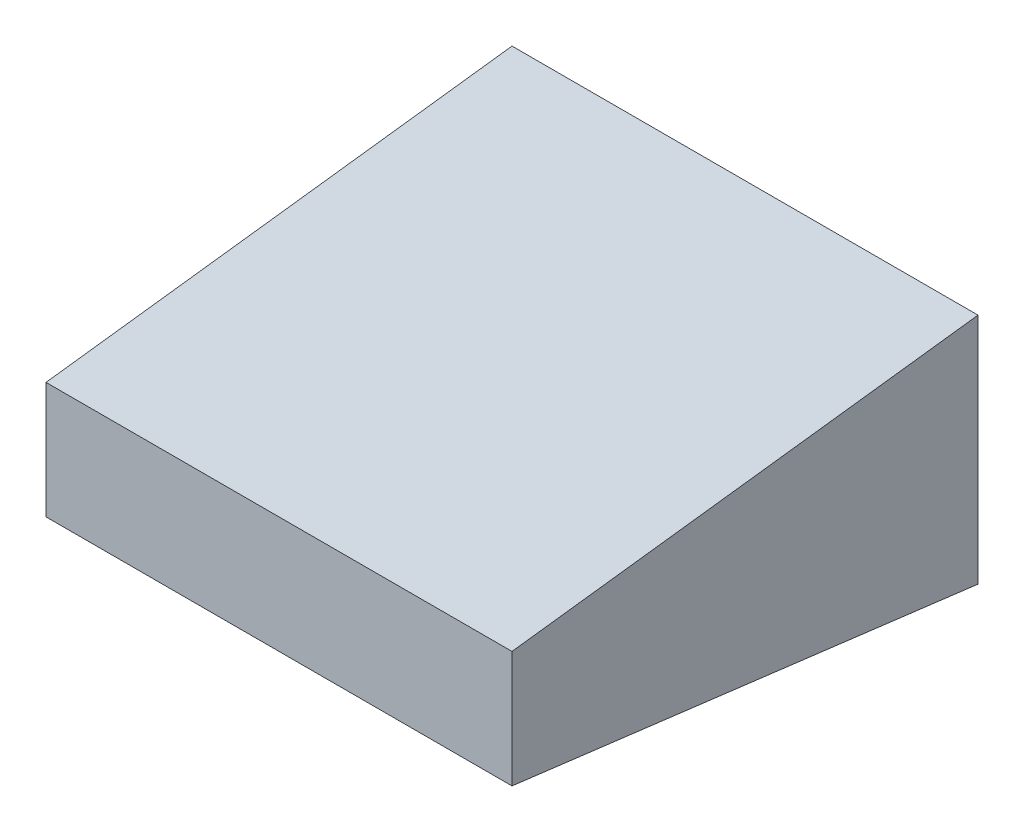
SolidWorks part; units mm, degrees
material "3.0205 (EN-AW 1200)"
ref_plane "Alzado" through (0, 0, 0) normal (0, 0, 1) x (1, 0, 0)
ref_plane "Planta" through (0, 0, 0) normal (0, 1, 0) x (1, 0, 0)
ref_plane "Vista lateral" through (0, 0, 0) normal (1, 0, 0) x (0, 0, -1)
sketch "Croquis1" plane through (0, 0, 0) normal (0, 0, 1) x (1, 0, 0)
  line L1 (-100, 50) -> (100, 50)
  line L2 (-100, 50) -> (-100, -50)
  line L3 (-100, -50) -> (100, -50)
  line L4 (100, 50) -> (100, -50)
  line L5 (-100, 50) -> (100, -50) construction
  line L6 (-100, -50) -> (100, 50) construction
  point P0 (0, 0)
extrude "Saliente-Extruir1" add sketch "Croquis1" along normal blind 200 contours L1 L4 L3 L2
sketch "Croquis18" plane through (-100, 0, 0) normal (-1, 0, 0) x (0, 0, 1)
  line L0 (0, 50) -> (200, 50)
  line L1 (200, 50) -> (200, 25)
  line L2 (200, 50) -> (200, -50) construction
  line L3 (200, 25) -> (0, 50)
extrude "Cortar-Extruir1" cut sketch "Croquis18" against normal blind 200 contours L3 L0 L1
sketch "Croquis20" plane through (-100, 0, 0) normal (-1, 0, 0) x (0, 0, 1)
  line L0 (0, -50) -> (200, -50)
  line L1 (200, -50) -> (200, -25)
  line L2 (200, 25) -> (200, -50) construction
  line L3 (200, -25) -> (0, -50)
extrude "Cortar-Extruir2" cut sketch "Croquis20" against normal blind 200
shell "Vaciado1" thickness 4
